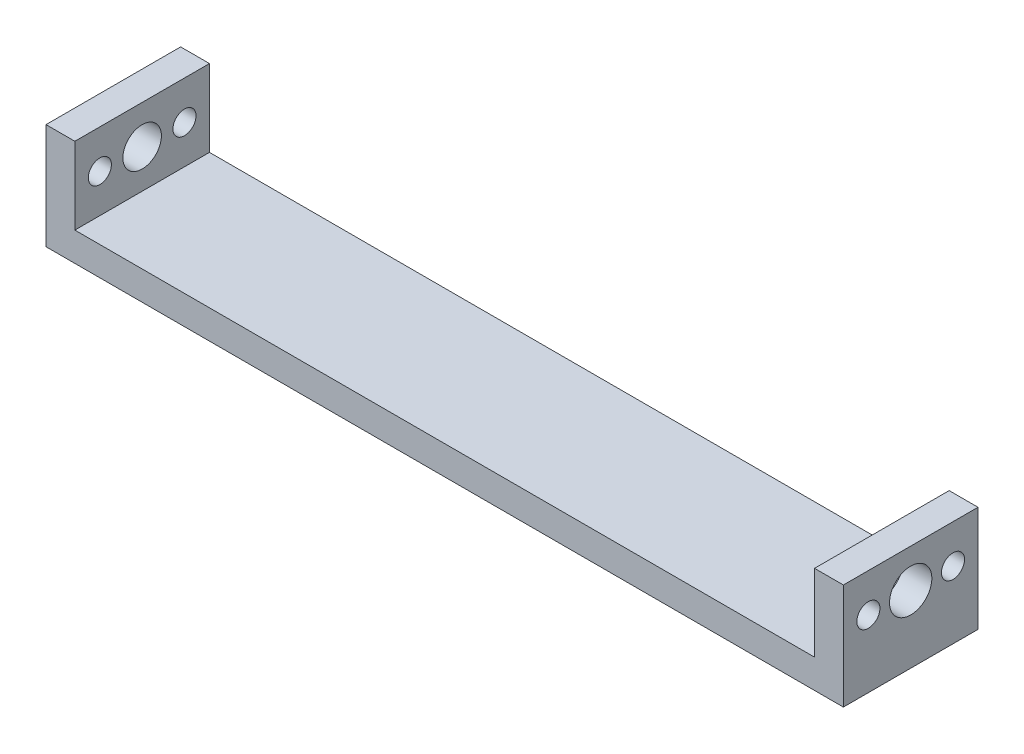
SolidWorks part; units mm, degrees
ref_plane "Front Plane" through (0, 0, 0) normal (0, 0, 1) x (1, 0, 0)
ref_plane "Top Plane" through (0, 0, 0) normal (0, 1, 0) x (1, 0, 0)
ref_plane "Right Plane" through (0, 0, 0) normal (1, 0, 0) x (0, 0, -1)
sketch "Sketch1" plane through (0, 0, 0) normal (0, 0, 1) x (1, 0, 0)
  line L0 (-207.9529, 0) -> (176.6471, 0)
  line L1 (176.6471, 0) -> (176.6471, 40)
  line L2 (-207.9529, 0) -> (-207.9529, 40)
  line L3 (-207.9529, 40) -> (-222.9529, 40)
  line L4 (-222.9529, 40) -> (-222.9529, 0)
  line L5 (-222.9529, 0) -> (-222.9529, -15)
  line L6 (-222.9529, -15) -> (191.6471, -15)
  line L7 (191.6471, -15) -> (191.6471, 0)
  line L8 (191.6471, 0) -> (191.6471, 40)
  line L9 (191.6471, 40) -> (176.6471, 40)
  dimension "D1" = 414.6
  dimension "D2" = 15
  dimension "D3" = 40
  dimension "D4" = 176.6471
  dimension "D5" = 15
extrude "Boss-Extrude3" add sketch "Sketch1" along normal blind 70
sketch "Sketch2" plane through (-207.9529, 0, 0) normal (1, 0, 0) x (0, 0, -1)
  line L0 (-35, 40) -> (-35, 0) construction
  line L1 (-70, 40) -> (0, 40) construction
  line L2 (-70, 0) -> (0, 0) construction
  line L3 (-70, 20) -> (0, 20) construction
  line L6 (-70, 0) -> (-70, 40) construction
  line L7 (0, 0) -> (0, 40) construction
  circle A0 centre (-35, 20) radius 10
  dimension "D1" = 20
extrude "Cut-Extrude1" cut sketch "Sketch2" against normal through all
sketch "Sketch3" plane through (-207.9529, 0, 0) normal (1, 0, 0) x (0, 0, -1)
  line L0 (-35, 40) -> (-35, 0) construction
  line L1 (-70, 40) -> (0, 40) construction
  line L2 (-70, 0) -> (0, 0) construction
  line L3 (0, 20) -> (-70, 20) construction
  line L4 (0, 0) -> (0, 40) construction
  line L5 (-70, 0) -> (-70, 40) construction
  circle A0 centre (-13, 20) radius 6
  circle A1 centre (-57, 20) radius 6
  dimension "D3" = 12
  dimension "D1" = 22
  dimension "D2" = 22
extrude "Cut-Extrude2" cut sketch "Sketch3" against normal through all
sketch "Sketch4" plane through (176.6471, 0, 0) normal (-1, 0, 0) x (0, 0, 1)
  line L0 (35, 40) -> (35, 0) construction
  line L1 (70, 40) -> (0, 40) construction
  line L2 (70, 0) -> (0, 0) construction
  line L3 (0, 20) -> (70, 20) construction
  line L4 (0, 40) -> (0, 0) construction
  line L5 (70, 40) -> (70, 0) construction
  circle A0 centre (35, 20) radius 11
  dimension "D1" = 22
extrude "Cut-Extrude3" cut sketch "Sketch4" against normal through all
sketch "Sketch5" plane through (176.6471, 0, 0) normal (-1, 0, 0) x (0, 0, 1)
  line L0 (35, 40) -> (35, 0) construction
  line L1 (70, 40) -> (0, 40) construction
  line L2 (70, 0) -> (0, 0) construction
  line L3 (0, 20) -> (70, 20) construction
  line L4 (0, 40) -> (0, 0) construction
  line L5 (70, 40) -> (70, 0) construction
  circle A0 centre (57, 20) radius 6
  circle A1 centre (13, 20) radius 6
  dimension "D3" = 12
  dimension "D1" = 22
  dimension "D2" = 22
extrude "Cut-Extrude4" cut sketch "Sketch5" against normal through all
